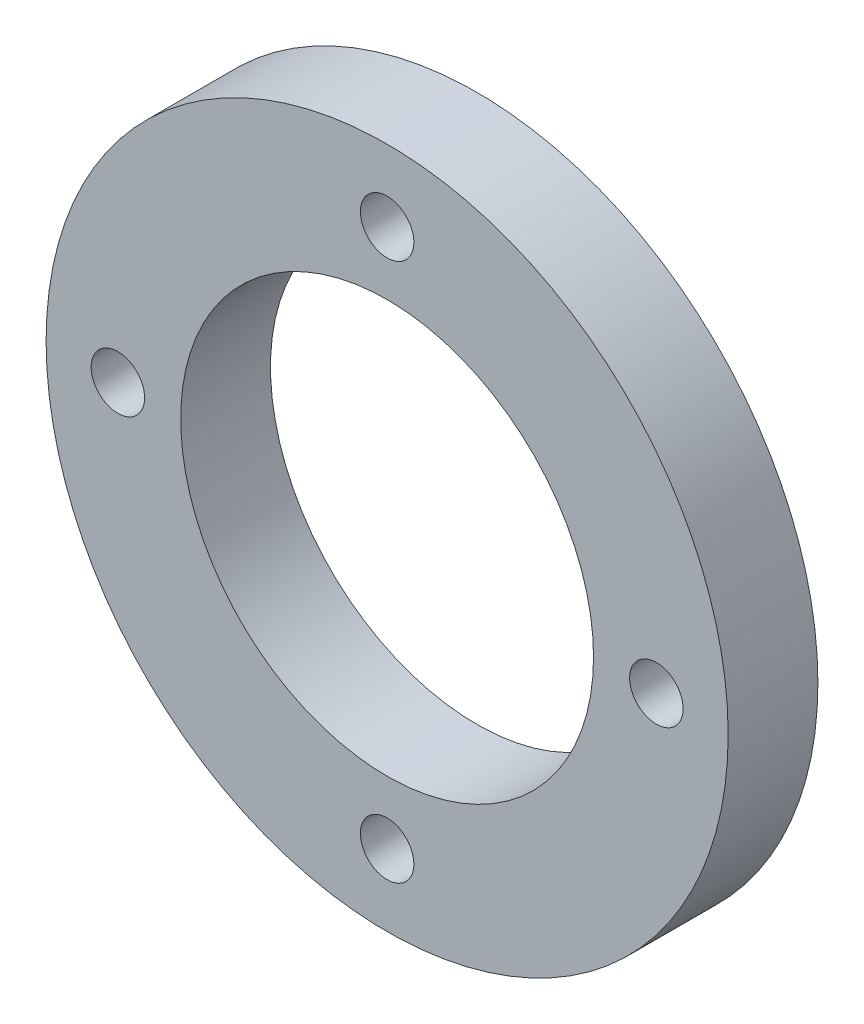
SolidWorks part; units mm, degrees
ref_plane "Front" through (0, 0, 0) normal (0, 0, 1) x (1, 0, 0)
ref_plane "Top" through (0, 0, 0) normal (0, 1, 0) x (1, 0, 0)
ref_plane "Right" through (0, 0, 0) normal (1, 0, 0) x (0, 0, -1)
sketch "Sketch1" plane through (0, 0, 0) normal (0, 0, 1) x (1, 0, 0)
  line L0 (-32.5019, 0) -> (34.1972, 0) construction
  circle A0 centre (0, 0) radius 11.5
  circle A1 centre (0, 0) radius 15 construction
  circle A2 centre (0, 0) radius 19
  circle A3 centre (0, 15) radius 1.49
  circle A4 centre (15, 0) radius 1.49
  circle A5 centre (0, -15) radius 1.49
  circle A6 centre (-15, 0) radius 1.49
  point P17 (0, 0)
  point P18 (0, -11.5)
  dimension "D1" = 23
  dimension "D2" = 30
  dimension "D3" = 38
  dimension "D4" = 2.98
  dimension "D5" = 4
extrude "Boss-Extrude1" add sketch "Sketch1" along normal blind 5 contours A2 A6 A5 A4 A3 A0
